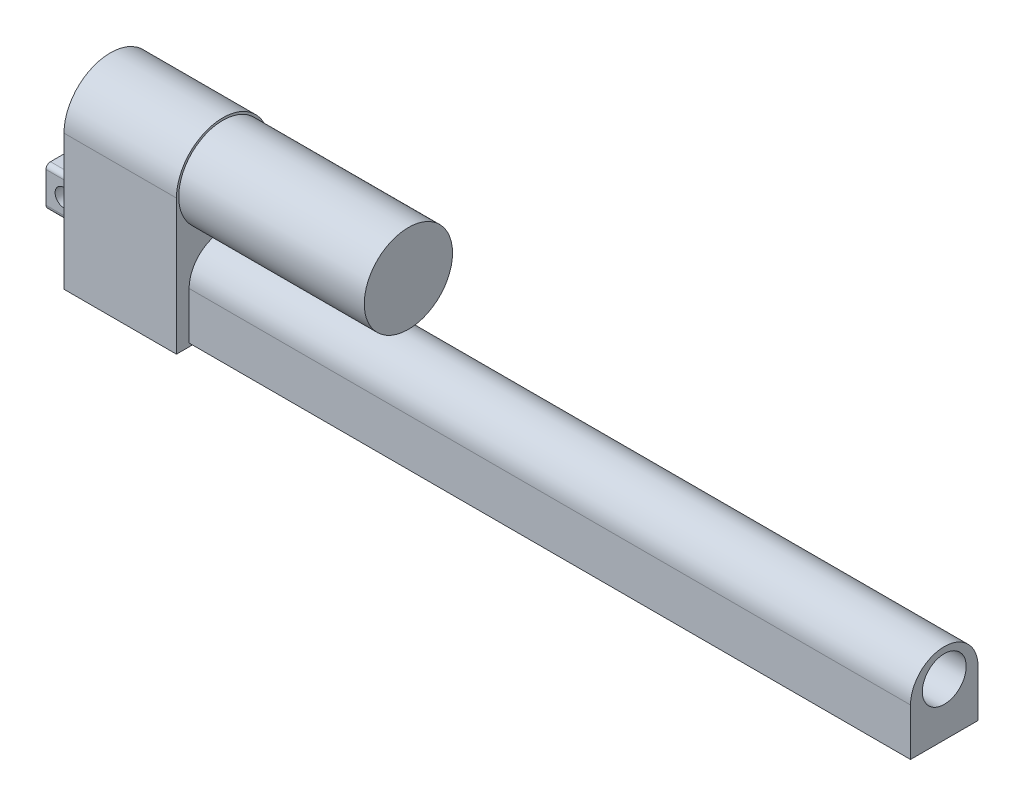
SolidWorks part; units mm, degrees
ref_plane "Front Plane" through (0, 0, 0) normal (0, 0, 1) x (1, 0, 0)
ref_plane "Top Plane" through (0, 0, 0) normal (0, 1, 0) x (1, 0, 0)
ref_plane "Right Plane" through (0, 0, 0) normal (1, 0, 0) x (0, 0, -1)
sketch "Sketch1" plane through (0, 0, 0) normal (1, 0, 0) x (0, 0, -1)
  line L2 (-20.955, 0) -> (-20.955, -61.087)
  line L3 (-20.955, -61.087) -> (20.955, -61.087)
  line L4 (20.955, 0) -> (20.955, -61.087)
  arc A0 (20.955, 0) -> (-20.955, 0) centre (0, 0) ccw
  dimension "D1" = 41.91
  dimension "D2" = 61.087
extrude "Boss-Extrude1" add sketch "Sketch1" along normal blind 50.8
sketch "Sketch2" plane through (50.8, 0, 0) normal (1, 0, 0) x (0, 0, -1)
  circle A0 centre (0, 0) radius 19.939
  dimension "D1" = 39.878
extrude "Boss-Extrude2" add sketch "Sketch2" along normal blind 83.82
sketch "Sketch3" plane through (50.8, 0, 0) normal (1, 0, 0) x (0, 0, -1)
  line L0 (-20.955, -61.087) -> (20.955, -61.087) construction
  line L1 (-15.24, -38.227) -> (15.24, -38.227)
  line L2 (-15.24, -38.227) -> (-15.24, -59.563)
  line L3 (-15.24, -59.563) -> (15.24, -59.563)
  line L4 (15.24, -38.227) -> (15.24, -59.563)
  arc A0 (15.24, -38.227) -> (-15.24, -38.227) centre (0, -38.227) ccw
  dimension "D1" = 30.48
  dimension "D2" = 21.336
  dimension "D3" = 22.86
extrude "Boss-Extrude3" add sketch "Sketch3" along normal blind 325.882 contours L1 A0 | L4 L1 L2 L3
sketch "Sketch4" plane through (0, 0, 0) normal (-1, 0, 0) x (0, 0, 1)
  line L0 (20.955, -61.087) -> (-20.955, -61.087) construction
  line L1 (-9.017, -28.194) -> (9.017, -28.194)
  line L2 (-9.017, -28.194) -> (-9.017, -46.228)
  line L3 (-9.017, -46.228) -> (9.017, -46.228)
  line L4 (9.017, -28.194) -> (9.017, -46.228)
  point P4 (0, -28.194)
  point P7 (-9.017, -37.211)
  dimension "D1" = 18.034
  dimension "D2" = 23.876
extrude "Boss-Extrude4" add sketch "Sketch4" along normal blind 20.066
sketch "Sketch5" plane through (0, 0, 9.017) normal (0, 0, 1) x (1, 0, 0)
  line L0 (0, -46.228) -> (0, -28.194) construction
  circle A0 centre (-11.938, -37.211) radius 4.0132
  point P4 (0, -37.211)
  dimension "D1" = 8.0264
  dimension "D2" = 11.938
fillet "Fillet2" radius 2.032 4 edges at (-10.033, -46.228, 9.017) (-10.033, -46.228, -9.017) (-10.033, -28.194, -9.017) (-10.033, -28.194, 9.017)
extrude "Cut-Extrude1" cut sketch "Sketch5" against normal through all
sketch "Sketch6" plane through (376.682, 0, 0) normal (1, 0, 0) x (0, 0, -1)
  line L0 (-15.24, -59.563) -> (15.24, -59.563) construction
  circle A0 centre (0, -35.687) radius 9.906
  point P4 (0, -59.563)
  dimension "D1" = 19.812
  dimension "D2" = 23.876
extrude "Cut-Extrude2" cut sketch "Sketch6" against normal blind 317.5
